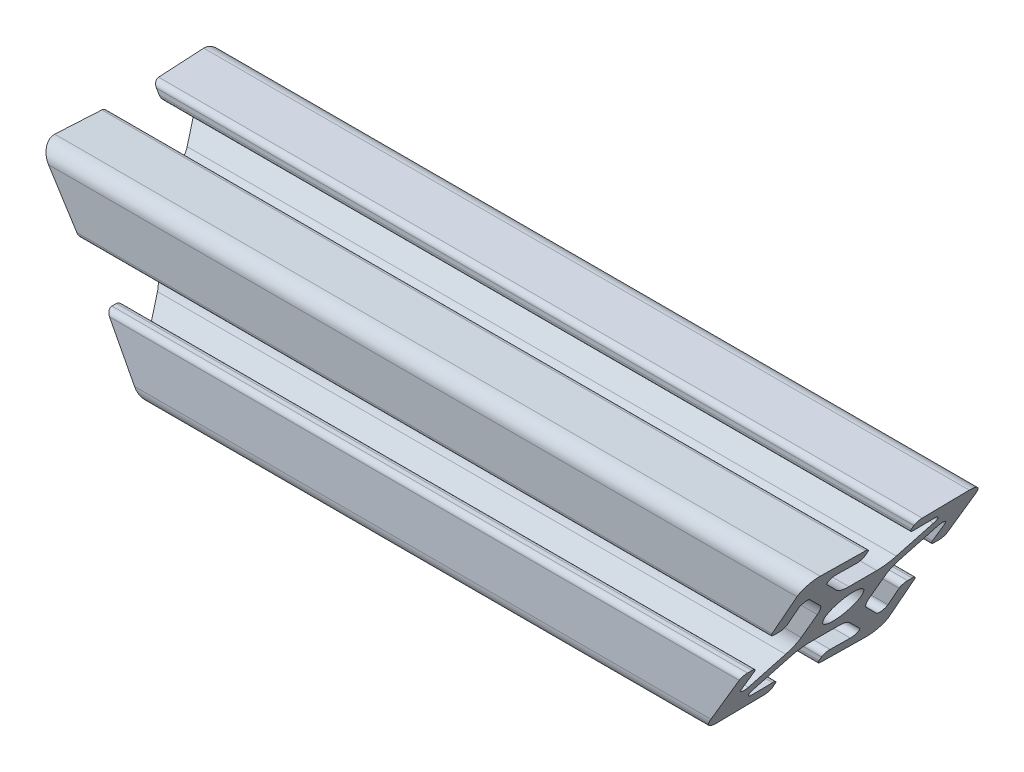
SolidWorks part; units mm, degrees
material "6061-T6 (SS)"
ref_plane "Front Plane" through (0, 0, 0) normal (0, 0, 1) x (1, 0, 0)
ref_plane "Top Plane" through (0, 0, 0) normal (0, 1, 0) x (1, 0, 0)
ref_plane "Right Plane" through (0, 0, 0) normal (1, 0, 0) x (0, 0, -1)
sketch "Sketch1" plane through (0, 0, 0) normal (1, 0, 0) x (0, 0, -1)
  line L0 (0, -12.7) -> (0, 12.7) construction
  line L1 (-7.874, 12.7) -> (7.874, 12.7) construction
  line L2 (-12.7, 0) -> (12.7, 0) construction
  line L3 (-7.874, 12.7) -> (-7.874, 4.826) construction
  line L4 (-3.302, 12.7) -> (3.302, 12.7) construction
  line L5 (-12.7, -12.7) -> (12.7, -12.7) construction
  line L6 (-12.7, 12.7) -> (12.7, 12.7) construction
  circle A0 centre (0, 0) radius 2.54 construction
  point P7 (0, 12.7)
  point P10 (0, 0)
  point P13 (0, 0)
  point P16 (0, 12.7)
  point P17 (-3.302, 12.7)
  point P18 (3.302, 12.7)
  point P21 (0, -12.7)
  point P24 (0, 12.7)
  dimension "Center Hole Diameter" = 5.08
  dimension "Rail Width" = 25.4
  dimension "Rail Height" = 25.4
  dimension "T-Slot Depth" = 7.874
  dimension "D1" = 15.748
  dimension "T-Slot Width" = 6.604
  dimension "D2" = 12.7
sketch "Sketch2" plane through (0, 0, 0) normal (0, 0, 1) x (1, 0, 0)
  line L0 (-54.4473, 0) -> (54.4473, 0) construction
  line L1 (0, 0) -> (0, 26.104) construction
  line L2 (54.4473, -12.7) -> (54.4473, 12.7) construction
  line L3 (-54.4473, -12.7) -> (-54.4473, 12.7) construction
  point P3 (-16.3473, 0)
  point P8 (0, 0)
  point P9 (16.3473, 0)
  point P12 (54.4473, 0)
  point P15 (-54.4473, 0)
  dimension "Length" = 108.8946
  dimension "D1" = 38.1
  dimension "D2" = 25.4
sketch "Sketch3" plane through (0, 0, 0) normal (1, 0, 0) x (0, 0, -1)
  line L0 (0, 4.826) -> (1.9842, 4.826)
  line L1 (0, -12.7) -> (0, 12.7) construction
  line L2 (4.2293, 5.7559) -> (7.5866, 9.1132)
  line L6 (7.0212, 10.4136) -> (4.0906, 10.3112)
  line L7 (3.302, 11.0728) -> (3.302, 11.7082)
  line L8 (-7.874, 12.7) -> (7.874, 12.7) construction
  line L10 (0, 0) -> (12.7, 12.7) construction
  line L13 (0, 4.826) -> (0, 2.54)
  line L14 (4.826, 0) -> (2.54, 0)
  line L31 (4.826, 0) -> (4.826, 1.9842)
  line L32 (4.0374, 12.4697) -> (10.5971, 12.6988)
  line L33 (-12.7, 0) -> (12.7, 0) construction
  line L34 (-12.7, 12.7) -> (12.7, 12.7) construction
  line L35 (5.7559, 4.2293) -> (9.1132, 7.5866)
  line L36 (0, 12.7) -> (12.7, 12.7) construction
  line L37 (12.7, 12.7) -> (12.7, 8.0234) construction
  line L38 (11.0728, 3.302) -> (11.7082, 3.302)
  line L39 (10.4136, 7.0212) -> (10.3112, 4.0906)
  line L40 (12.6988, 10.5971) -> (12.4697, 4.0374)
  arc A0 (2.54, 0) -> (0, 2.54) centre (0, 0) ccw
  arc A1 (1.9842, 4.826) -> (4.2293, 5.7559) centre (1.9842, 8.001) ccw
  circle A2 centre (0, 0) radius 2.54 construction
  arc A7 (3.302, 11.7082) -> (4.0374, 12.4697) centre (4.064, 11.7082) cw
  arc A8 (4.0906, 10.3112) -> (3.302, 11.0728) centre (4.064, 11.0728) cw
  arc A14 (4.826, 1.9842) -> (5.7559, 4.2293) centre (8.001, 1.9842) cw
  arc A16 (10.5971, 12.6988) -> (12.6988, 10.5971) centre (10.668, 10.668) cw
  arc A17 (7.0212, 10.4136) -> (7.5866, 9.1132) centre (7.0478, 9.652) cw
  arc A18 (10.4136, 7.0212) -> (9.1132, 7.5866) centre (9.652, 7.0478) ccw
  arc A19 (10.3112, 4.0906) -> (11.0728, 3.302) centre (11.0728, 4.064) ccw
  arc A20 (11.7082, 3.302) -> (12.4697, 4.0374) centre (11.7082, 4.064) ccw
  point P37 (3.2994, 4.826)
  point P49 (12.7, 3.302)
  point P52 (3.302, 12.7)
  point P55 (3.302, 10.2837)
  dimension "D4" = 3.175
  dimension "D9" = 2.159
  dimension "D12" = 0.762
  dimension "D3" = 2.032
  dimension "D8" = 0.762
  dimension "D2" = 45
  dimension "D5" = 2
  dimension "D6" = 45
  dimension "D7" = 2.159
extrude "Boss-Extrude1" add sketch "Sketch3" against normal up to vertex (54.4473 mm away) and the other way up to vertex (54.4473 mm away) up to point (-54.4473, 0, 0) other way up to point (54.4473, 0, 0)
mirror "Mirror1" about plane through (0, 0, 0) normal (0, 1, 0) of bodies 104
mirror "Mirror2" about plane through (0, 0, 0) normal (0, 0, 1) of bodies 105
sketch "Sketch4" plane through (0, 0, 0) normal (0, 0, 1) x (1, 0, 0)
  line L1 (-56.9873, -38.1) -> (56.9873, -38.1)
  line L3 (54.4473, 12.7) -> (39.7826, -12.7)
  line L4 (39.7826, -12.7) -> (-39.7826, -12.7)
  line L5 (-39.7826, -12.7) -> (-54.4473, 12.7)
  line L6 (-54.4473, 12.7) -> (-56.9873, 12.7)
  line L7 (-56.9873, 12.7) -> (-56.9873, -38.1)
  line L8 (54.4473, 12.7) -> (56.9873, 12.7)
  line L9 (56.9873, 12.7) -> (56.9873, -38.1)
  dimension "D2" = 25.4
  dimension "D4" = 25.4
  dimension "D1" = 2.54
  dimension "D3" = 2.54
  dimension "D5" = 30
  dimension "D6" = 30
extrude "Cut-Extrude1" cut sketch "Sketch4" along normal blind 12.7 and the other way blind 12.7 contours L1 L9 L8 L3 L4 L5 L6 L7
ref_plane "Plane1" through (0, 12.6988, 0) normal (0, -1, 0) x (-1, 0, 0)
ref_plane "Plane2" through (0, 0, -12.6988) normal (0, 0, -1) x (-1, 0, 0)
ref_plane "Plane3" through (0, -12.6988, 0) normal (0, 1, 0) x (1, 0, 0)
ref_plane "Plane4" through (0, 0, 12.6988) normal (0, 0, -1) x (-1, 0, 0)
equation "\"D1@Sketch2\"=\"Rail Height@Sketch1\"*1.5"
equation "\"D2@Sketch2\"=\"Rail Height@Sketch1\""
equation "\"MaxLength\"= ( \"ROVWidth@Assem2.SLDASM\" - ( 2 * \"ROVLength@Assem2.SLDASM\" ) * TAN ( \"Theta@Assem2.SLDASM\" ) + ( TAN ( \"Theta@Assem2.SLDASM\" ) / TAN ( \"Phi@Assem2.SLDASM\" ) ) * ( \"ROVWidth@Assem2.SLDASM\" - \"FaceWidth@Assem2.SLDASM\" ) )"
equation "\"Length@Sketch2\"= \"MaxLength\""
equation "\"LeftCutAngle\"= 45 - ( \"Theta@Assem2.SLDASM\" / 2 )"
equation "\"RightCutAngle\"= \"LeftCutAngle\""
equation "\"BarThickness\"= 1in"
equation "\"InnerLength\"= \"MaxLength\" - TAN ( \"LeftCutAngle\" ) - TAN ( \"RightCutAngle\" )"
equation "\"RightBevelLength\"= tan ( \"RightCutAngle\" )"
equation "\"D2@Sketch4\"=\"BarThickness\""
equation "\"D4@Sketch4\"=\"BarThickness\""
equation "\"D1@Cut-Extrude1\"=\"BarThickness\"/2"
equation "\"D2@Cut-Extrude1\"=\"BarThickness\"/2"
equation "\"D5@Sketch4\"=\"LeftCutAngle\""
equation "\"D6@Sketch4\"=\"RightCutAngle\""
